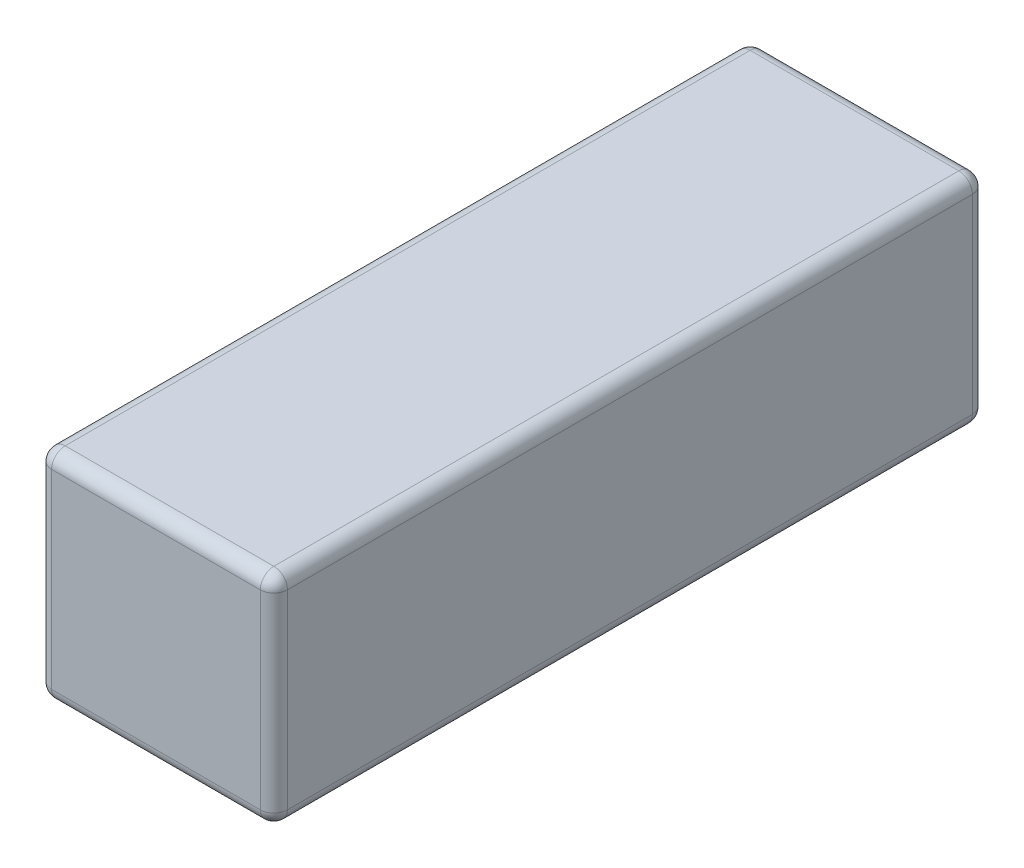
SolidWorks part; units mm, degrees
ref_plane "Front Plane" through (0, 0, 0) normal (0, 0, 1) x (1, 0, 0)
ref_plane "Top Plane" through (0, 0, 0) normal (0, 1, 0) x (1, 0, 0)
ref_plane "Right Plane" through (0, 0, 0) normal (1, 0, 0) x (0, 0, -1)
sketch "Sketch1" plane through (0, 0, 0) normal (0, 0, 1) x (1, 0, 0)
  line L1 (0, 0) -> (52, 0)
  line L2 (0, 0) -> (0, 48)
  line L3 (0, 48) -> (52, 48)
  line L4 (52, 0) -> (52, 48)
  dimension "D1" = 52
  dimension "D2" = 48
extrude "Boss-Extrude1" add sketch "Sketch1" along normal blind 157
fillet "Fillet1" radius 3 12 edges at (52, 0, 78.5) (52, 24, 0) (26, 0, 0) (0, 0, 78.5) (0, 24, 0) (26, 48, 0) (52, 48, 78.5) (52, 24, 157) (26, 0, 157) (0, 24, 157) (26, 48, 157) (0, 48, 78.5)
